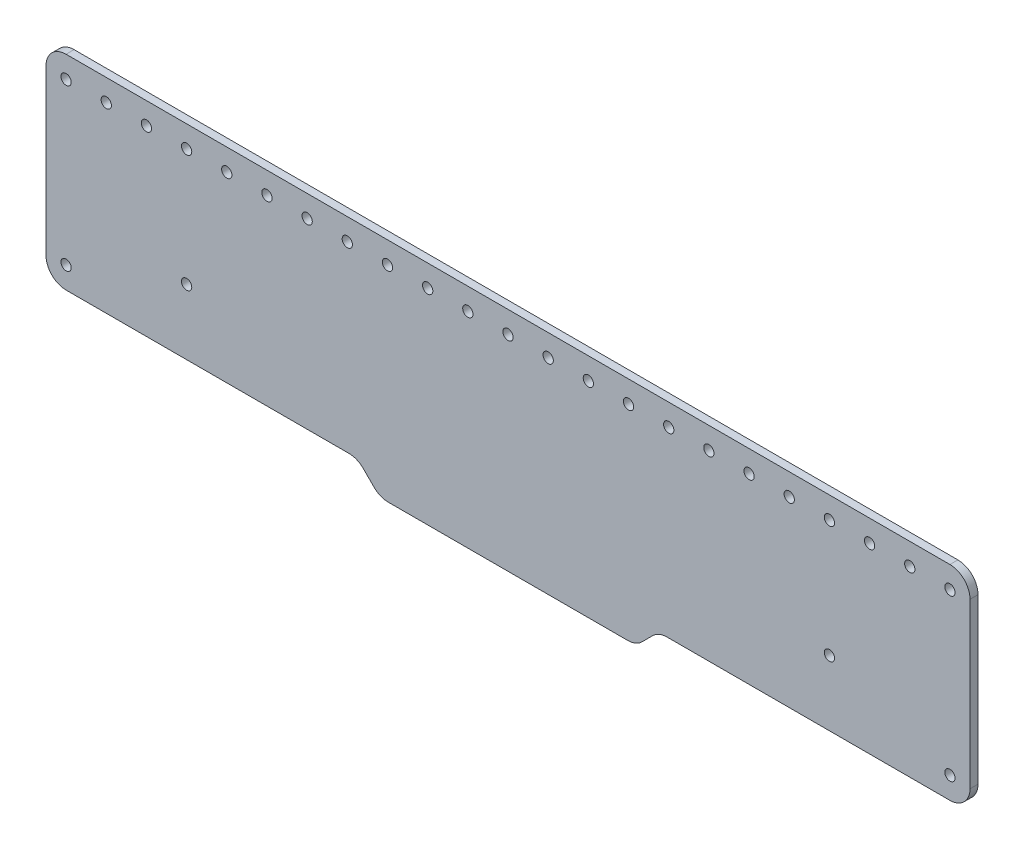
SolidWorks part; units mm, degrees
ref_plane "Front Plane" through (0, 0, 0) normal (0, 0, 1) x (1, 0, 0)
ref_plane "Top Plane" through (0, 0, 0) normal (0, 1, 0) x (1, 0, 0)
ref_plane "Right Plane" through (0, 0, 0) normal (1, 0, 0) x (0, 0, -1)
sketch "Sketch1" plane through (0, 0, 0) normal (0, 0, 1) x (1, 0, 0)
  line L0 (-184, -10.175) -> (184, -10.175) construction
  line L1 (184, 45.175) -> (-184, 45.175)
  line L2 (184, 45.175) -> (184, -45.175)
  line L3 (184, -45.175) -> (-184, -45.175)
  line L4 (-184, 45.175) -> (-184, -45.175)
  line L5 (184, 45.175) -> (-184, -45.175) construction
  line L6 (184, -45.175) -> (-184, 45.175) construction
  line L7 (0, 0) -> (0, -50000) construction
  line L8 (-184, 42) -> (49816, 42) construction
  line L9 (-128, 8.925) -> (-30.5044, 8.925) construction
  line L10 (-128, -29.275) -> (-30.5044, -29.275) construction
  line L11 (-127.8953, -58.1749) -> (-83.2354, -58.0775) construction
  line L12 (50, -40.175) -> (-50, -40.175) construction
  line L13 (50, -40.175) -> (50, 19.825) construction
  line L14 (50, 19.825) -> (-50, 19.825) construction
  line L15 (-50, -40.175) -> (-50, 19.825) construction
  line L16 (50, -40.175) -> (-50, 19.825) construction
  line L17 (50, 19.825) -> (-50, -40.175) construction
  line L18 (-46.5044, 5.825) -> (-14.5044, 5.825) construction
  line L19 (-46.5044, 5.825) -> (-46.5044, -26.175) construction
  line L20 (-46.5044, -26.175) -> (-14.5044, -26.175) construction
  line L21 (-14.5044, 5.825) -> (-14.5044, -26.175) construction
  line L22 (-46.5044, 5.825) -> (-14.5044, -26.175) construction
  line L23 (-46.5044, -26.175) -> (-14.5044, 5.825) construction
  circle A0 centre (-128, -10.175) radius 48 construction
  circle A1 centre (-30.5044, -10.175) radius 18 construction
  circle A3 centre (-128, -10.175) radius 19.1 construction
  circle A4 centre (-30.5044, -10.175) radius 19.1 construction
  arc A5 (-128, 8.925) -> (-128, -29.275) centre (-128, -10.175) ccw construction
  arc A6 (-30.5044, 8.925) -> (-30.5044, -29.275) centre (-30.5044, -10.175) cw construction
  circle A7 centre (-128, -10.175) radius 2.05
  circle A8 centre (128, -10.175) radius 2.05
  circle A9 centre (30.5044, -10.175) radius 18 construction
  circle A10 centre (-50, 19.825) radius 2.05 construction
  circle A11 centre (50, 19.825) radius 2.05 construction
  circle A12 centre (50, -40.175) radius 2.05 construction
  circle A13 centre (-50, -40.175) radius 2.05 construction
  circle A14 centre (-46.5044, 5.825) radius 2.05 construction
  circle A15 centre (-14.5044, 5.825) radius 2.05 construction
  circle A16 centre (-14.5044, -26.175) radius 2.05 construction
  circle A17 centre (-46.5044, -26.175) radius 2.05 construction
  circle A18 centre (46.5044, 5.825) radius 2.05 construction
  circle A19 centre (14.5044, 5.825) radius 2.05 construction
  circle A20 centre (46.5044, -26.175) radius 2.05 construction
  circle A21 centre (14.5044, -26.175) radius 2.05 construction
  point P0 (0, 0)
  point P16 (0, -10.175)
  dimension "D3" = 96
  dimension "D4" = 36
  dimension "D8" = 38.2
  dimension "D10" = 4.1
  dimension "D13" = 4.1
  dimension "D1" = 368
  dimension "D2" = 90.35
  dimension "D5" = 3.175
  dimension "D7" = 56
  dimension "D11" = 60
  dimension "D12" = 100
  dimension "D14" = 32
  dimension "D15" = 32
  dimension "D6" = 55.35
extrude "Boss-Extrude1" add sketch "Sketch1" along normal blind 3.175
sketch "Sketch3" plane through (0, 0, 3.175) normal (0, 0, 1) x (1, 0, 0)
  line L0 (0, 0) -> (0, -50000) construction
  line L1 (0, 0) -> (50000, 0) construction
  line L2 (-82.0903, 42) -> (49917.9097, 42) construction
  line L3 (184, 45.175) -> (-184, 45.175) construction
  line L4 (-151.5131, 36.5) -> (49848.4869, 36.5) construction
  line L5 (-176, 161.8742) -> (-176, -49838.1258) construction
  line L6 (-184, 45.175) -> (-184, -45.175) construction
  line L7 (-159.635, -36.175) -> (49840.365, -36.175) construction
  line L9 (-176, 36.5) -> (-160, 36.5) construction
  line L10 (-176, 36.5) -> (-176, 20.5) construction
  line L11 (-150.701, -33) -> (49849.299, -33) construction
  circle A0 centre (-176, 36.5) radius 2.05
  circle A5 centre (-160, 36.5) radius 2.05
  circle A6 centre (-144, 36.5) radius 2.05
  circle A7 centre (-128, 36.5) radius 2.05
  circle A8 centre (-112, 36.5) radius 2.05
  circle A9 centre (-96, 36.5) radius 2.05
  circle A10 centre (-80, 36.5) radius 2.05
  circle A11 centre (-64, 36.5) radius 2.05
  circle A12 centre (-48, 36.5) radius 2.05
  circle A13 centre (-32, 36.5) radius 2.05
  circle A14 centre (-16, 36.5) radius 2.05
  circle A15 centre (0, 36.5) radius 2.05
  circle A16 centre (16, 36.5) radius 2.05
  circle A17 centre (32, 36.5) radius 2.05
  circle A18 centre (48, 36.5) radius 2.05
  circle A19 centre (64, 36.5) radius 2.05
  circle A20 centre (80, 36.5) radius 2.05
  circle A21 centre (96, 36.5) radius 2.05
  circle A22 centre (112, 36.5) radius 2.05
  circle A23 centre (128, 36.5) radius 2.05
  circle A24 centre (144, 36.5) radius 2.05
  circle A25 centre (160, 36.5) radius 2.05
  circle A26 centre (176, 36.5) radius 2.05
  circle A27 centre (-160, 20.5) radius 2.05 construction
  circle A28 centre (-144, 20.5) radius 2.05 construction
  circle A29 centre (-128, 20.5) radius 2.05 construction
  circle A30 centre (-112, 20.5) radius 2.05 construction
  circle A31 centre (-96, 20.5) radius 2.05 construction
  circle A32 centre (-80, 20.5) radius 2.05 construction
  circle A33 centre (-64, 20.5) radius 2.05 construction
  circle A34 centre (-48, 20.5) radius 2.05 construction
  circle A35 centre (-32, 20.5) radius 2.05 construction
  circle A36 centre (-16, 20.5) radius 2.05 construction
  circle A37 centre (0, 20.5) radius 2.05 construction
  circle A38 centre (16, 20.5) radius 2.05 construction
  circle A39 centre (32, 20.5) radius 2.05 construction
  circle A40 centre (48, 20.5) radius 2.05 construction
  circle A41 centre (64, 20.5) radius 2.05 construction
  circle A42 centre (80, 20.5) radius 2.05 construction
  circle A43 centre (96, 20.5) radius 2.05 construction
  circle A44 centre (112, 20.5) radius 2.05 construction
  circle A45 centre (128, 20.5) radius 2.05 construction
  circle A46 centre (144, 20.5) radius 2.05 construction
  circle A47 centre (160, 20.5) radius 2.05 construction
  circle A48 centre (176, 20.5) radius 2.05 construction
  circle A49 centre (-160, 4.5) radius 2.05 construction
  circle A50 centre (-144, 4.5) radius 2.05 construction
  circle A51 centre (-128, 4.5) radius 2.05 construction
  circle A52 centre (-112, 4.5) radius 2.05 construction
  circle A53 centre (-96, 4.5) radius 2.05 construction
  circle A54 centre (-80, 4.5) radius 2.05 construction
  circle A55 centre (-64, 4.5) radius 2.05 construction
  circle A56 centre (-48, 4.5) radius 2.05 construction
  circle A57 centre (-32, 4.5) radius 2.05 construction
  circle A58 centre (-16, 4.5) radius 2.05 construction
  circle A59 centre (0, 4.5) radius 2.05 construction
  circle A60 centre (16, 4.5) radius 2.05 construction
  circle A61 centre (32, 4.5) radius 2.05 construction
  circle A62 centre (48, 4.5) radius 2.05 construction
  circle A63 centre (64, 4.5) radius 2.05 construction
  circle A64 centre (80, 4.5) radius 2.05 construction
  circle A65 centre (96, 4.5) radius 2.05 construction
  circle A66 centre (112, 4.5) radius 2.05 construction
  circle A67 centre (128, 4.5) radius 2.05 construction
  circle A68 centre (144, 4.5) radius 2.05 construction
  circle A69 centre (160, 4.5) radius 2.05 construction
  circle A70 centre (176, 4.5) radius 2.05 construction
  circle A71 centre (-160, -11.5) radius 2.05 construction
  circle A72 centre (-144, -11.5) radius 2.05 construction
  circle A73 centre (-128, -11.5) radius 2.05 construction
  circle A74 centre (-112, -11.5) radius 2.05 construction
  circle A75 centre (-96, -11.5) radius 2.05 construction
  circle A76 centre (-80, -11.5) radius 2.05 construction
  circle A77 centre (-64, -11.5) radius 2.05 construction
  circle A78 centre (-48, -11.5) radius 2.05 construction
  circle A79 centre (-32, -11.5) radius 2.05 construction
  circle A80 centre (-16, -11.5) radius 2.05 construction
  circle A81 centre (0, -11.5) radius 2.05 construction
  circle A82 centre (16, -11.5) radius 2.05 construction
  circle A83 centre (32, -11.5) radius 2.05 construction
  circle A84 centre (48, -11.5) radius 2.05 construction
  circle A85 centre (64, -11.5) radius 2.05 construction
  circle A86 centre (80, -11.5) radius 2.05 construction
  circle A87 centre (96, -11.5) radius 2.05 construction
  circle A88 centre (112, -11.5) radius 2.05 construction
  circle A89 centre (128, -11.5) radius 2.05 construction
  circle A90 centre (144, -11.5) radius 2.05 construction
  circle A91 centre (160, -11.5) radius 2.05 construction
  circle A92 centre (176, -11.5) radius 2.05 construction
  circle A93 centre (-160, -27.5) radius 2.05 construction
  circle A94 centre (-144, -27.5) radius 2.05 construction
  circle A95 centre (-128, -27.5) radius 2.05 construction
  circle A96 centre (-112, -27.5) radius 2.05 construction
  circle A97 centre (-96, -27.5) radius 2.05 construction
  circle A98 centre (-80, -27.5) radius 2.05 construction
  circle A99 centre (-64, -27.5) radius 2.05 construction
  circle A100 centre (-48, -27.5) radius 2.05 construction
  circle A101 centre (-32, -27.5) radius 2.05 construction
  circle A102 centre (-16, -27.5) radius 2.05 construction
  circle A103 centre (0, -27.5) radius 2.05 construction
  circle A104 centre (16, -27.5) radius 2.05 construction
  circle A105 centre (32, -27.5) radius 2.05 construction
  circle A106 centre (48, -27.5) radius 2.05 construction
  circle A107 centre (64, -27.5) radius 2.05 construction
  circle A108 centre (80, -27.5) radius 2.05 construction
  circle A109 centre (96, -27.5) radius 2.05 construction
  circle A110 centre (112, -27.5) radius 2.05 construction
  circle A111 centre (128, -27.5) radius 2.05 construction
  circle A112 centre (144, -27.5) radius 2.05 construction
  circle A113 centre (160, -27.5) radius 2.05 construction
  circle A114 centre (176, -27.5) radius 2.05
  circle A137 centre (-176, 20.5) radius 2.05 construction
  circle A138 centre (-176, 4.5) radius 2.05 construction
  circle A139 centre (-176, -11.5) radius 2.05 construction
  circle A140 centre (-176, -27.5) radius 2.05
  dimension "D1" = 3.175
  dimension "D4" = 4.1
  dimension "D2" = 5.5
  dimension "D3" = 8
  dimension "D7" = 16
  dimension "D8" = 16
  dimension "D9" = 16
  dimension "D10" = 22.6274
  dimension "D11" = 5.5
  dimension "D12" = 3.175
  dimension "D5" = 23
  dimension "D6" = 5
extrude "Cut-Extrude1" cut sketch "Sketch3" against normal blind 3.18
sketch "Sketch4" plane through (0, 0, 3.175) normal (0, 0, 1) x (1, 0, 0)
  line L0 (0, 0) -> (0, -50000) construction
  line L1 (-39.7115, -36.18) -> (49960.2885, -36.18) construction
  line L2 (-184, -36.18) -> (-60, -36.18)
  line L3 (-60, -36.18) -> (-51.005, -45.175)
  line L4 (-184, -45.175) -> (184, -45.175) construction
  line L5 (-184, -36.18) -> (-184, -45.175)
  line L6 (-184, -45.175) -> (-51.005, -45.175)
  line L7 (184, -36.18) -> (184, -45.175)
  line L8 (184, -36.18) -> (60, -36.18)
  line L9 (60, -36.18) -> (51.005, -45.175)
  line L10 (184, -45.175) -> (51.005, -45.175)
  line L11 (-184, 45.175) -> (-184, -45.175) construction
  circle A0 centre (-176, -27.5) radius 2.05 construction
  dimension "D1" = 8.68
  dimension "D2" = 60
  dimension "D3" = 45
extrude "Cut-Extrude2" cut sketch "Sketch4" against normal blind 10
fillet "Fillet1" radius 8 8 edges at (184, 45.175, 1.5875) (-184, 45.175, 1.5875) (184, -36.18, 1.5875) (51.005, -45.175, 1.5875) (60, -36.18, 1.5875) (-51.005, -45.175, 1.5875) (-60, -36.18, 1.5875) (-184, -36.18, 1.5875)
equation "\"w\"= 368mm"
equation "\"D1@Sketch1\"=\"w\""
equation "\"border\"= 8mm"
equation "\"h\"= 84mm + \"thick\" * 2"
equation "\"D2@Sketch1\"=\"h\""
equation "\"thick\"= 3.175mm"
equation "\"D5@Sketch1\"=\"thick\""
equation "\"innerMotorDiameter\"= 32mm"
equation "\"D4@Sketch1\"=\"innerMotorDiameter\" + 4mm"
equation "\"outerMotorDiameter\"= 38mm"
equation "\"pitchDiameter\"= 38.2mm"
equation "\"D8@Sketch1\"=\"pitchDiameter\""
equation "\"pathLength\"= 315mm'63 Tooth GoBilda Belt"
equation "\"D9@Sketch1\"=\"pathLength\""
equation "\"sh\"= 4.1mm"
equation "\"D10@Sketch1\"=\"sh\""
equation "\"D1@Boss-Extrude1\"=\"thick\""
equation "\"D1@Sketch3\"=\"thick\""
equation "\"D4@Sketch3\"=\"sh\""
equation "\"D2\"= \"thick\""
equation "\"D12@Sketch3\"=\"thick\""
